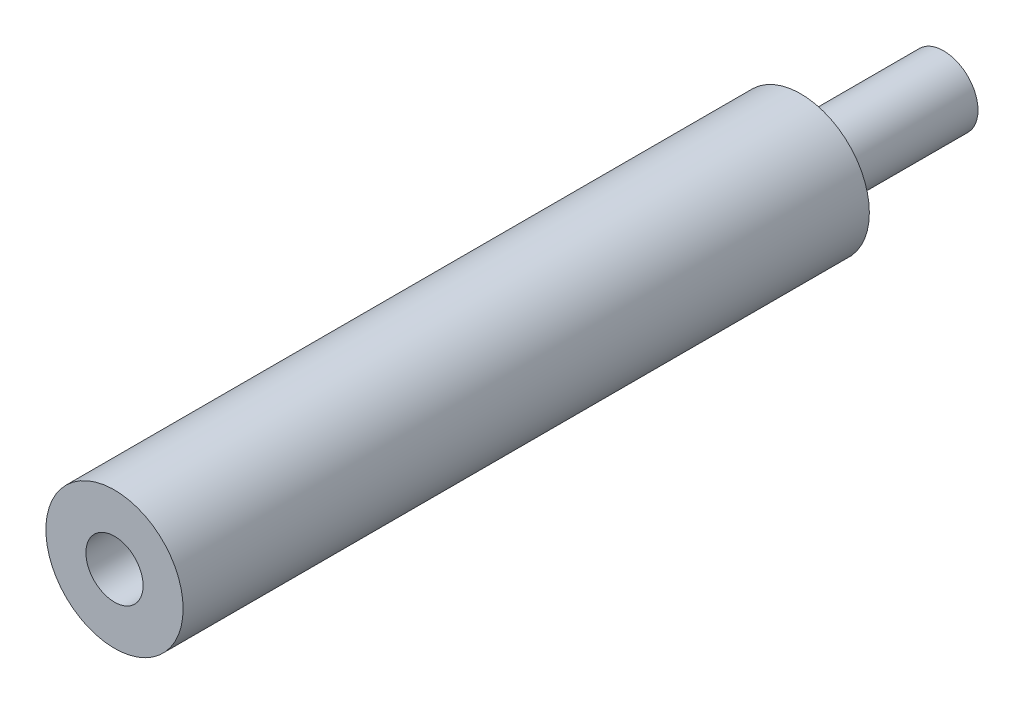
SolidWorks part; units mm, degrees
ref_plane "前视基准面" through (0, 0, 0) normal (0, 0, 1) x (1, 0, 0)
ref_plane "上视基准面" through (0, 0, 0) normal (0, 1, 0) x (1, 0, 0)
ref_plane "右视基准面" through (0, 0, 0) normal (1, 0, 0) x (0, 0, -1)
sketch "草图1" plane through (0, 0, 0) normal (0, 0, 1) x (1, 0, 0)
  circle A0 centre (0, 0) radius 6
  dimension "D2" = 12
extrude "凸台-拉伸1" add sketch "草图1" along normal mid plane 60
sketch "草图2" plane through (0, 0, -30) normal (0, 0, -1) x (-1, 0, 0)
  circle A3 centre (0, 0) radius 3
  circle A4 centre (0, 0) radius 3
  dimension "D1" = 3
extrude "凸台-拉伸2" add sketch "草图2" along normal offset from surface (12.5 mm away) 5
sketch "草图4" plane through (0, 0, 30) normal (0, 0, 1) x (1, 0, 0)
  circle A2 centre (0, 0) radius 2.5
  circle A3 centre (0, 0) radius 2.5
  dimension "D1" = 0.5
extrude "切除-拉伸1" cut sketch "草图4" against normal blind 10
